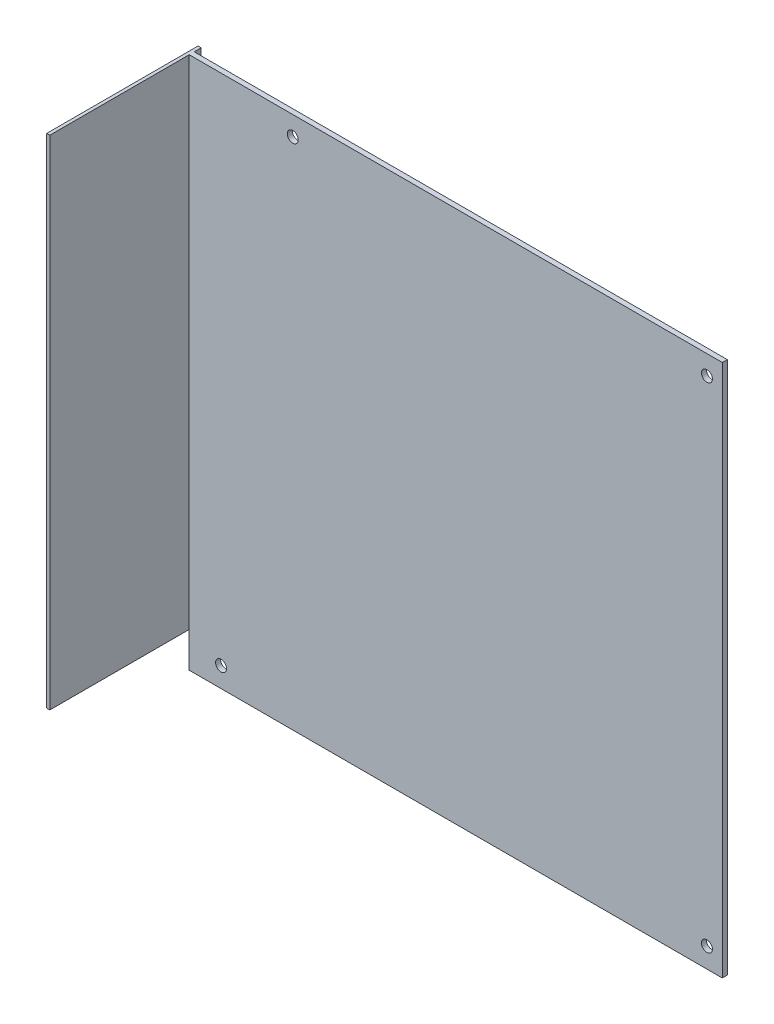
SolidWorks part; units mm, degrees
ref_plane "前视基准面" through (0, 0, 0) normal (0, 0, 1) x (1, 0, 0)
ref_plane "上视基准面" through (0, 0, 0) normal (0, 1, 0) x (1, 0, 0)
ref_plane "右视基准面" through (0, 0, 0) normal (1, 0, 0) x (0, 0, -1)
other "Configuration Table"
sketch "草图1" plane through (0, 0, 0) normal (0, 0, 1) x (1, 0, 0)
  line L0 (0, 0) -> (170, 0)
  line L1 (170, 0) -> (170, 170)
  line L2 (170, 170) -> (0, 170)
  line L3 (0, 170) -> (0, 0)
  dimension "D1" = 170
  dimension "D2" = 170
extrude "凸台-拉伸1" add sketch "草图1" along normal blind 1.6
sketch "草图2" plane through (0, 0, 1.6) normal (0, 0, 1) x (1, 0, 0)
  line L4 (0, 170) -> (0, 0)
  line L5 (0, 0) -> (170, 0)
  line L6 (170, 0) -> (170, 170)
  line L7 (170, 170) -> (0, 170)
  line L8 (0, 170) -> (0, 0)
  line L9 (0, 0) -> (170, 0)
  line L10 (170, 0) -> (170, 170)
  line L11 (170, 170) -> (0, 170)
  circle A0 centre (10.16, 6.35) radius 1.75
  circle A1 centre (165.1, 6.35) radius 1.75
  circle A2 centre (165.1, 163.83) radius 1.75
  circle A3 centre (33.02, 163.83) radius 1.75
  point P6 (0, 0)
  point P7 (0, 0)
  point P10 (-9.3629, 6.4219)
  point P11 (18.7621, 6.35)
  point P12 (0, 0)
  point P15 (165.1, 39.4947)
  point P16 (0, 0)
  point P19 (56.7711, 163.83)
  point P20 (0, 0)
  dimension "D2" = 3.5
  dimension "D6" = 3.5
  dimension "D7" = 157.48
  dimension "D8" = 3.5
  dimension "D10" = 3.5
  dimension "D3" = 10.16
  dimension "D4" = 6.35
  dimension "D5" = 154.94
  dimension "D9" = 22.86
  dimension "D1" = 0
extrude "切除-拉伸2" cut sketch "草图2" against normal through all contours A0 | A1 | A2 | A3
sketch "草图5" plane through (0, 0, 1.6) normal (0, 0, 1) x (1, 0, 0)
  line L0 (0, 170) -> (-1, 170)
  line L1 (-1, 170) -> (-1, 11.25)
  line L2 (-1, 11.25) -> (0, 11.25)
  line L4 (0, 170) -> (0, 0)
  line L5 (0, 0) -> (170, 0)
  line L6 (170, 0) -> (170, 170)
  line L7 (170, 170) -> (0, 170)
  line L8 (0, 170) -> (0, 0)
  line L9 (0, 0) -> (170, 0)
  line L10 (170, 0) -> (170, 170)
  line L11 (170, 170) -> (0, 170)
  line M11 (0, 170) -> (0, 0)
  dimension "D2" = 1
  dimension "D3" = 158.75
  dimension "D1" = 0
extrude "凸台-拉伸2" add sketch "草图5" along normal blind 44.45 and the other way blind 3.81 contours L1 L2 L0 M11
